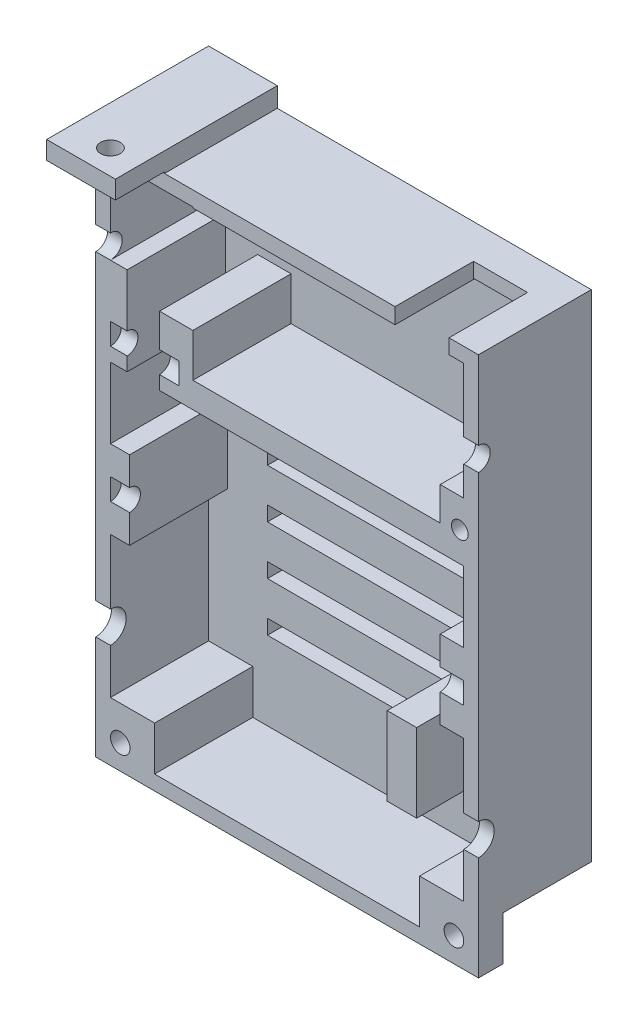
SolidWorks part; units mm, degrees
ref_plane "前视基准面" through (0, 0, 0) normal (0, 0, 1) x (1, 0, 0)
ref_plane "上视基准面" through (0, 0, 0) normal (0, 1, 0) x (1, 0, 0)
ref_plane "右视基准面" through (0, 0, 0) normal (1, 0, 0) x (0, 0, -1)
other "Configuration Table"
sketch "草图1" plane through (0, 0, 0) normal (0, 0, 1) x (1, 0, 0)
  line L1 (19.5, 27.5) -> (-19.5, 27.5)
  line L2 (19.5, 27.5) -> (19.5, -27.5)
  line L3 (19.5, -27.5) -> (-19.5, -27.5)
  line L4 (-19.5, 27.5) -> (-19.5, -27.5)
  line L5 (19.5, 27.5) -> (-19.5, -27.5) construction
  line L6 (19.5, -27.5) -> (-19.5, 27.5) construction
  point P0 (0, 0)
  dimension "D1" = 55
  dimension "D2" = 39
extrude "凸台-拉伸1" add sketch "草图1" along normal blind 11.5
shell "抽壳1" thickness 1.5
sketch "草图2" plane through (0, 0, 0) normal (0, 0, -1) x (-1, 0, 0)
  line L0 (-19.5, 27.5) -> (19.5, 27.5) construction
  line L1 (19.5, 29.5) -> (12.5, 29.5)
  line L2 (19.5, 29.5) -> (19.5, 27.5)
  line L3 (19.5, 27.5) -> (12.5, 27.5)
  line L4 (12.5, 29.5) -> (12.5, 27.5)
  line L6 (19.5, 27.5) -> (19.5, -27.5) construction
  dimension "D2" = 2
  dimension "D3" = 7
extrude "凸台-拉伸2" add sketch "草图2" against normal offset from surface (16.5 mm away) 5 separate body up to face at (0, 0, 11.5) offset beyond the face yes
sketch "草图3" plane through (0, 29.5, 0) normal (0, 1, 0) x (1, 0, 0)
  circle A0 centre (-15.502, -14) radius 1
  dimension "D1" = 2
extrude "切除-拉伸1" cut sketch "草图3" against normal up to next (2 mm away)
sketch "草图4" plane through (0, 27.5, 0) normal (0, 1, 0) x (1, 0, 0)
  line L0 (19.5, -11.5) -> (-19.5, -11.5) construction
  line L1 (11, -3.5) -> (16.5, -3.5)
  line L2 (11, -3.5) -> (11, -11.5)
  line L3 (11, -11.5) -> (16.5, -11.5)
  line L4 (16.5, -3.5) -> (16.5, -11.5)
  line L5 (16.5, -7.5) -> (16.5, -3.5) construction
extrude "切除-拉伸2" cut sketch "草图4" against normal up to next (1.5 mm away)
sketch "草图5" plane through (-19.5, 0, 0) normal (-1, 0, 0) x (0, 0, 1)
  circle A0 centre (11.5, 18.3) radius 1.2
  arc A1 (11.5, 17.1) -> (11.5, 19.5) centre (11.5, 18.3) ccw construction
  circle A3 centre (11.5, -15.3) radius 1.6
  arc A4 (11.5, -16.9) -> (11.5, -13.7) centre (11.5, -15.3) ccw construction
extrude "切除-拉伸3" cut sketch "草图5" against normal through all
sketch "草图8" plane through (0, 0, 0) normal (0, 0, -1) x (-1, 0, 0)
  line L0 (18, 0.9) -> (16.05, 0.9) construction
  line L1 (16.05, -7.1) -> (18, -7.1) construction
  line L6 (-18, -7.1) -> (-15.6, -7.1) construction
  line L7 (-15.6, 0.9) -> (-18, 0.9) construction
  line L8 (-15.6, 14.1) -> (-18, 14.1) construction
  line L9 (-15.6, 10.7) -> (-15.6, 14.1) construction
  line L10 (9.6, 10.7) -> (-15.6, 10.7) construction
  line L11 (9.6, 15.1) -> (9.6, 10.7) construction
  line L12 (-18, 8.1) -> (13, 8.1) construction
  line L13 (13, 15.1) -> (9.6, 15.1) construction
  line L14 (16.3, 8.1) -> (18, 8.1) construction
  line L15 (18, 17.1) -> (16.3, 17.1) construction
  line L16 (18, 0.9) -> (16.05, 0.9)
  line L17 (16.05, -7.1) -> (18, -7.1)
  line L22 (-18, -7.1) -> (-15.6, -7.1)
  line L23 (-15.6, 0.9) -> (-18, 0.9)
  line L24 (-15.6, 14.1) -> (-18, 14.1)
  line L25 (-15.6, 10.7) -> (-15.6, 14.1)
  line L26 (9.6, 10.7) -> (-15.6, 10.7)
  line L27 (9.6, 15.1) -> (9.6, 10.7)
  line L28 (-18, 8.1) -> (13, 8.1)
  line L29 (13, 15.1) -> (9.6, 15.1)
  line L30 (16.3, 8.1) -> (18, 8.1)
  line L31 (18, 17.1) -> (16.3, 17.1)
  line L32 (18, 8.1) -> (18, 17.1)
  line L33 (16.3, 17.1) -> (16.3, 8.1)
  line L34 (13, 8.1) -> (13, 15.1)
  line L35 (-18, 14.1) -> (-18, 8.1)
  line L36 (-15.6, -7.1) -> (-15.6, 0.9)
  line L37 (-18, 0.9) -> (-18, -7.1)
  line L38 (18, -7.1) -> (18, 0.9)
  line L39 (16.05, 0.9) -> (16.05, -7.1)
  line L40 (18, -21.5) -> (13.5, -21.5) construction
  line L41 (13.5, -21.5) -> (13.5, -26) construction
  line L42 (-13.5, -26) -> (-13.5, -21.5) construction
  line L43 (-13.5, -21.5) -> (-18, -21.5) construction
  line L44 (18, -21.5) -> (13.5, -21.5)
  line L45 (13.5, -21.5) -> (13.5, -26)
  line L46 (-13.5, -26) -> (-13.5, -21.5)
  line L47 (-13.5, -21.5) -> (-18, -21.5)
  line L48 (18, -21.5) -> (18, -26)
  line L49 (18, -26) -> (13.5, -26)
  line L50 (-13.5, -26) -> (-18, -26)
  line L51 (-18, -26) -> (-18, -21.5)
  line L52 (-11, 25.9) -> (9.6, 25.9) construction
  line L53 (-11, 25.9) -> (9.6, 25.9)
  line L55 (9.6, 25.9) -> (9.6, 26)
  line L56 (9.6, 26) -> (-11, 26)
  line L57 (-11, 26) -> (-11, 25.9)
extrude "凸台-拉伸3" add sketch "草图8" against normal blind 11.5
sketch "草图7" plane through (-19.5, 0, 0) normal (-1, 0, 0) x (0, 0, 1)
  circle A0 centre (11.5, -3.1) radius 1.1
  dimension "D1" = 2.2
sketch "草图10" plane through (-19.5, 0, 0) normal (-1, 0, 0) x (0, 0, 1)
  circle A0 centre (11.5, 10.6) radius 1.1
  dimension "D1" = 2.2
extrude "切除-拉伸12" cut sketch "草图10" against normal blind 7 from offset 1.5 offset against normal yes
extrude "切除-拉伸13" cut sketch "草图7" against normal offset from surface (36 mm away) 1.5 from offset 1.5 up to face at (19.5, 0.75, 8.275) offset against normal yes
sketch "草图13" plane through (0, 0, 0) normal (0, 0, -1) x (-1, 0, 0)
  line L0 (13.5, -26) -> (-13.5, -26) construction
  line L1 (12, -16.5) -> (-12, -16.5)
  line L2 (12, -16.5) -> (12, -18)
  line L3 (12, -18) -> (-12, -18)
  line L4 (-12, -16.5) -> (-12, -18)
  line L5 (0, 0) -> (0, 20.7312) construction
  line L6 (12, -11.5) -> (-12, -11.5)
  line L7 (12, -11.5) -> (12, -13)
  line L8 (12, -13) -> (-12, -13)
  line L9 (-12, -11.5) -> (-12, -13)
  line L10 (12, -6.5) -> (-12, -6.5)
  line L11 (12, -6.5) -> (12, -8)
  line L12 (12, -8) -> (-12, -8)
  line L13 (-12, -6.5) -> (-12, -8)
  line L14 (12, -1.5) -> (-12, -1.5)
  line L15 (12, -1.5) -> (12, -3)
  line L16 (12, -3) -> (-12, -3)
  line L17 (-12, -1.5) -> (-12, -3)
  line L18 (12, 3.5) -> (-12, 3.5)
  line L19 (12, 3.5) -> (12, 2)
  line L20 (12, 2) -> (-12, 2)
  line L21 (-12, 3.5) -> (-12, 2)
  line L22 (12, 8.5) -> (-12, 8.5)
  line L23 (12, 8.5) -> (12, 7)
  line L24 (12, 7) -> (-12, 7)
  line L25 (-12, 8.5) -> (-12, 7)
  dimension "D1" = 1.5
  dimension "D2" = 8
  dimension "D3" = 24
  dimension "D4" = 6
extrude "切除-拉伸14" cut sketch "草图13" against normal blind 1.5
sketch "草图12" plane through (0, 0, 0) normal (0, 0, -1) x (-1, 0, 0)
  line L0 (-10.2, -19.55) -> (-7.2, -19.55) construction
  line L1 (-10.2, -11.55) -> (-10.2, -19.55) construction
  line L2 (-7.2, -11.55) -> (-10.2, -11.55) construction
  line L3 (-7.2, -19.55) -> (-7.2, -11.55) construction
  line L4 (-10.2, -19.55) -> (-7.2, -19.55)
  line L5 (-10.2, -11.55) -> (-10.2, -19.55)
  line L6 (-7.2, -11.55) -> (-10.2, -11.55)
  line L7 (-7.2, -19.55) -> (-7.2, -11.55)
extrude "凸台-拉伸4" add sketch "草图12" against normal blind 8.5
sketch "草图14" plane through (0, 0, 16.5) normal (0, 0, 1) x (1, 0, 0)
  line L0 (-19.5, 29.5) -> (-19.5, 27.5) construction
  line L1 (-19.5, 27.65) -> (-12.5, 27.65)
  line L2 (-19.5, 27.65) -> (-19.5, 27.5)
  line L3 (-19.5, 27.5) -> (-12.5, 27.5)
  line L4 (-12.5, 27.65) -> (-12.5, 27.5)
  dimension "D1" = 0.15
extrude "切除-拉伸15" cut sketch "草图14" against normal up to surface (5 mm away) up to face at (-9.025, 24.725, 11.5)
sketch "草图15" plane through (0, 0, 0) normal (0, 0, -1) x (-1, 0, 0)
  line L0 (19.5, -27.5) -> (-19.5, -27.5) construction
  line L1 (15, -23) -> (19.5, -23)
  line L2 (15, -23) -> (15, -27.5)
  line L3 (15, -27.5) -> (19.5, -27.5)
  line L4 (19.5, -23) -> (19.5, -27.5)
  line L5 (-15, -23) -> (-19.5, -23)
  line L6 (-15, -23) -> (-15, -27.5)
  line L7 (-15, -27.5) -> (-19.5, -27.5)
  line L8 (-19.5, -23) -> (-19.5, -27.5)
  line L9 (-19.5, -27.5) -> (-19.5, 27.5) construction
  line L10 (-13.5, -26) -> (-13.5, -21.5) construction
  line L11 (-13.5, -21.5) -> (-18, -21.5) construction
  line L12 (13.5, -21.5) -> (13.5, -26) construction
  line L13 (18, -21.5) -> (13.5, -21.5) construction
  dimension "D1" = 1.5
  dimension "D2" = 1.5
  dimension "D3" = 1.5
  dimension "D4" = 1.5
extrude "切除-拉伸16" cut sketch "草图15" against normal offset from surface (9 mm away) 2.5 up to face at (-9.025, 24.725, 11.5)
sketch "草图16" plane through (0, 0, 9) normal (0, 0, -1) x (-1, 0, 0)
  circle A0 centre (-17, -25) radius 1
  circle A1 centre (17, -25) radius 1
  dimension "D1" = 2
  dimension "D2" = 2
extrude "切除-拉伸17" cut sketch "草图16" against normal up to next (2.5 mm away)
sketch "草图17" plane through (0, 0, 0) normal (0, 0, -1) x (-1, 0, 0)
  circle A0 centre (-17.6, 11.1) radius 0.85
  dimension "D1" = 1.7
extrude "切除-拉伸18" cut sketch "草图17" along normal blind 2.5 from surface at -11.5 starting at face at (18, 24.3333, 11.5)
